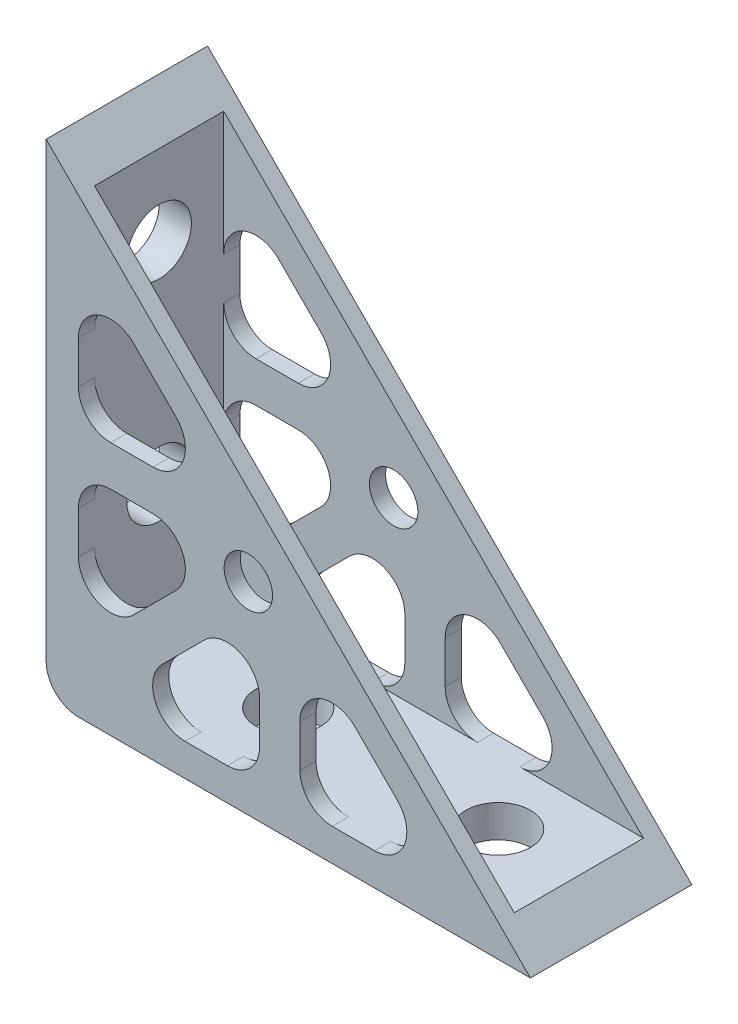
SolidWorks part; units mm, degrees
material "6061 Alloy"
ref_plane "Front Plane" through (0, 0, 0) normal (0, 0, 1) x (1, 0, 0)
ref_plane "Top Plane" through (0, 0, 0) normal (0, 1, 0) x (1, 0, 0)
ref_plane "Right Plane" through (0, 0, 0) normal (1, 0, 0) x (0, 0, -1)
sketch "Sketch1" plane through (0, 0, 0) normal (0, 0, 1) x (1, 0, 0)
  line L0 (0, 0) -> (0, 30)
  line L1 (0, 30) -> (30, 0)
  line L2 (30, 0) -> (0, 0)
  dimension "D1" = 45
  dimension "D2" = 30
extrude "Boss-Extrude1" add sketch "Sketch1" along normal blind 10
sketch "Sketch2" plane through (0, 0, 0) normal (-1, 0, 0) x (0, 0, 1)
  line L0 (10, 0) -> (0, 0) construction
  line L1 (10, 30) -> (0, 30) construction
  circle A0 centre (5, 23) radius 2
  circle A1 centre (5, 10) radius 2
  point P5 (5, 0)
  dimension "D1" = 4
  dimension "D2" = 7
  dimension "D3" = 10
extrude "Cut-Extrude1" cut sketch "Sketch2" against normal through all both and the other way through all
sketch "Sketch3" plane through (0, 0, 0) normal (0, -1, 0) x (1, 0, 0)
  line L0 (0, 10) -> (0, 0) construction
  line L1 (30, 10) -> (30, 0) construction
  circle A0 centre (23, 5) radius 2
  circle A1 centre (10, 5) radius 2
  point P5 (0, 5)
  dimension "D1" = 4
  dimension "D3" = 10
  dimension "D2" = 7
extrude "Cut-Extrude2" cut sketch "Sketch3" against normal through all both and the other way through all
sketch "Sketch4" plane through (0, 0, 0) normal (0, -1, 0) x (1, 0, 0)
  line L0 (0, 10) -> (30, 10) construction
  line L1 (29, 9) -> (2, 9)
  line L2 (29, 9) -> (29, 1)
  line L3 (29, 1) -> (2, 1)
  line L4 (2, 9) -> (2, 1)
  line L5 (0, 0) -> (30, 0) construction
  line L6 (0, 10) -> (0, 0) construction
  line L7 (30, 10) -> (30, 0) construction
  dimension "D1" = 1
  dimension "D2" = 1
  dimension "D3" = 2
  dimension "D4" = 1
extrude "Cut-Extrude3" cut sketch "Sketch4" against normal through all from offset 2 offset against normal yes
sketch "Sketch6" plane through (0, 0, 0) normal (0, 0, -1) x (-1, 0, 0)
  line L0 (-25.1716, 2) -> (-15.7197, 11.4519)
  line L1 (-2, 25.1716) -> (-2, 15.7197)
  line L2 (-3.7678, 2) -> (-13.2197, 2)
  line L3 (-13.2197, 11.4519) -> (-3.7678, 2)
  line L4 (-2, 3.7678) -> (-11.4519, 13.2197)
  line L5 (-15.7197, 11.4519) -> (-15.7197, 2)
  line L6 (-13.2197, 11.4519) -> (-13.2197, 2)
  line L7 (-11.4519, 15.7197) -> (-2, 15.7197)
  line L8 (-11.4519, 13.2197) -> (-2, 13.2197)
  line L9 (-11.4519, 15.7197) -> (-2, 25.1716)
  line L10 (-15.7197, 2) -> (-25.1716, 2)
  line L11 (-2, 13.2197) -> (-2, 3.7678)
  line L12 (-30, 0) -> (0, 30) construction
  line L13 (0, 0) -> (-30, 0) construction
  line L14 (0, 30) -> (0, 0) construction
  line L15 (-11.4519, 13.2197) -> (-13.2197, 11.4519) construction
  line L16 (-2, 3.7678) -> (-3.7678, 2) construction
  line L17 (-15.7197, 6.726) -> (-13.2197, 6.726) construction
  line L18 (-6.726, 8.4937) -> (-8.4937, 6.726) construction
  line L19 (-6.726, 15.7197) -> (-6.726, 13.2197) construction
  line L20 (-12.3358, 12.3358) -> (-2.8839, 2.8839) construction
  dimension "D1" = 2
  dimension "D2" = 2
  dimension "D3" = 2
  dimension "D4" = 2.5
extrude "Cut-Extrude5" cut sketch "Sketch6" against normal through all both and the other way through all
fillet "Fillet1" radius 2 25 edges at (11.4519, 15.7197, 0.5) (13.2197, 11.4519, 0.5) (13.2197, 2, 0.5) (3.7678, 2, 0.5) (2, 13.2197, 0.5) (11.4519, 13.2197, 0.5) (2, 3.7678, 0.5) (15.7197, 2, 0.5) (15.7197, 11.4519, 0.5) (25.1716, 2, 0.5) (2, 25.1716, 0.5) (2, 15.7197, 0.5) (2, 15.7197, 9.5) (11.4519, 15.7197, 9.5) (2, 25.1716, 9.5) (13.2197, 2, 9.5) (13.2197, 11.4519, 9.5) (11.4519, 13.2197, 9.5) (2, 13.2197, 9.5) (2, 3.7678, 9.5) (15.7197, 11.4519, 9.5) (15.7197, 2, 9.5) (25.1716, 2, 9.5) (3.7678, 2, 9.5) (0, 0, 5)
sketch "Sketch7" plane through (0, 0, 0) normal (0, 0, -1) x (-1, 0, 0)
  line L0 (0, 0) -> (-12.5251, 12.5251) construction
  line L1 (-7.182, 5.4142) -> (-9.8055, 8.0377) construction
  line L2 (-8.0377, 19.1339) -> (-19.1339, 8.0377) construction
  circle A0 centre (-12.5251, 12.5251) radius 1.5
  dimension "D1" = 3
extrude "Cut-Extrude6" cut sketch "Sketch7" against normal through all both and the other way through all
